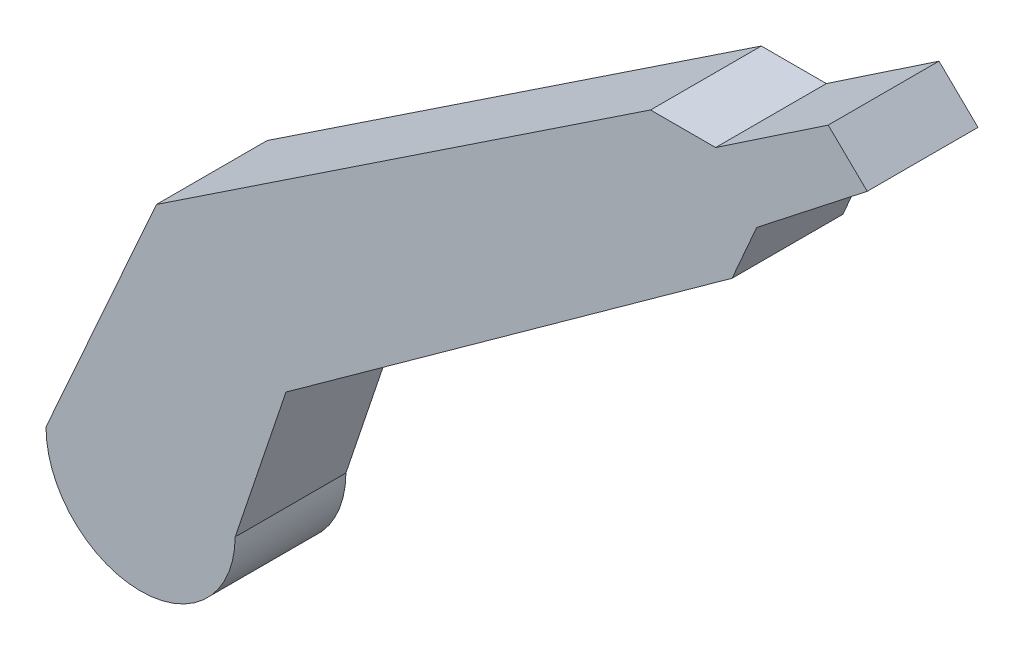
SolidWorks part; units mm, degrees
ref_plane "Front Plane" through (0, 0, 0) normal (0, 0, 1) x (1, 0, 0)
ref_plane "Top Plane" through (0, 0, 0) normal (0, 1, 0) x (1, 0, 0)
ref_plane "Right Plane" through (0, 0, 0) normal (1, 0, 0) x (0, 0, -1)
sketch "Sketch1" plane through (0, 0, 0) normal (0, 0, 1) x (1, 0, 0)
  line L0 (-4.967, 8.8358) -> (-71.885, -35.7072)
  line L1 (-71.885, -35.7072) -> (-86.8336, -69.2613)
  line L2 (6.0778, -5.3822) -> (-54.3404, -48.9366)
  line L3 (-54.3404, -48.9366) -> (-61.2186, -69.3668)
  line L4 (-4.967, 8.8358) -> (3.845, 8.8358)
  line L5 (3.845, 8.8358) -> (19.0919, 19.0919)
  line L6 (19.0919, 19.0919) -> (24.3771, 13.9638)
  line L7 (24.3771, 13.9638) -> (9.408, 2.2454)
  line L8 (9.408, 2.2454) -> (6.0778, -5.3822)
  arc A0 (-86.8336, -69.2613) -> (-61.2186, -69.3668) centre (-74.0261, -69.314) ccw
extrude "Boss-Extrude1" add sketch "Sketch1" against normal blind 15
sketch "Sketch2" plane through (0, 0, 0) normal (0, 0, 1) x (1, 0, 0)
  line L0 (-86.8336, -69.2613) -> (-61.2186, -69.3668)
  line L1 (-71.885, -35.7072) -> (-86.8336, -69.2613) construction
